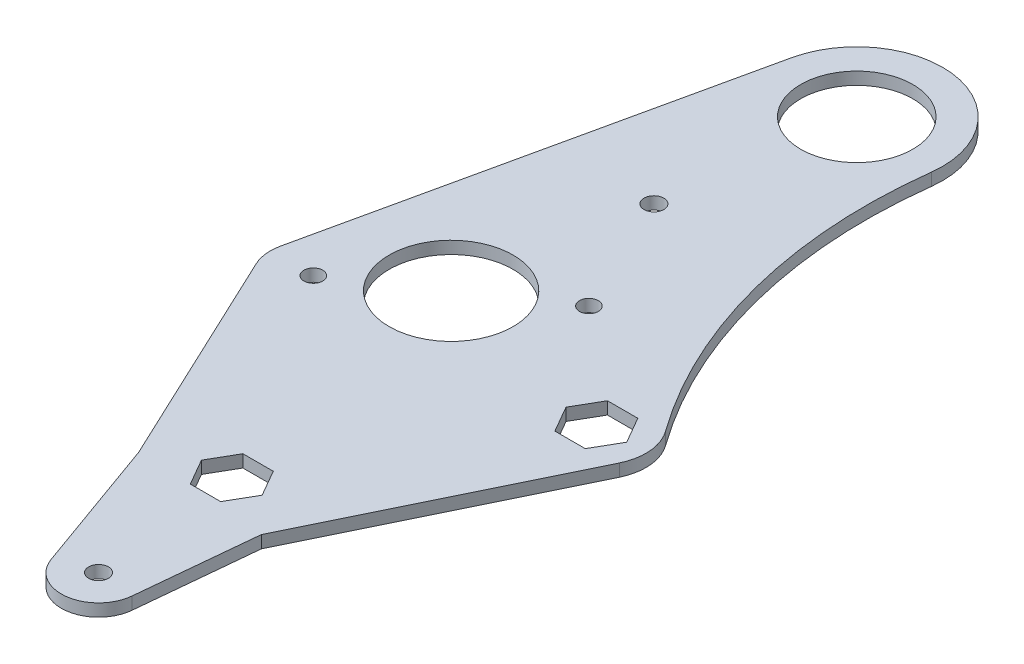
SolidWorks part; units mm, degrees
ref_plane "Front Plane" through (0, 0, 0) normal (0, 0, 1) x (1, 0, 0)
ref_plane "Top Plane" through (0, 0, 0) normal (0, 1, 0) x (1, 0, 0)
ref_plane "Right Plane" through (0, 0, 0) normal (1, 0, 0) x (0, 0, -1)
sketch "Sketch1" plane through (0, 0, 0) normal (0, 1, 0) x (1, 0, 0)
  line L0 (60.325, -101.6) -> (50.8, 0) construction
  line L1 (49.5334, -11.2731) -> (37.1501, -8.4548) construction
  line L2 (38.8111, -108.331) -> (42.6973, -101.6)
  line L3 (42.6973, -101.6) -> (38.8111, -94.869)
  line L4 (38.8111, -94.869) -> (31.0389, -94.869)
  line L5 (31.0389, -94.869) -> (27.1527, -101.6)
  line L6 (27.1527, -101.6) -> (31.0389, -108.331)
  line L7 (31.0389, -108.331) -> (38.8111, -108.331)
  line L12 (-34.3622, -104.78) -> (7.6653, -76.2435) construction
  line L13 (21.3295, 5.3232) -> (47.247, -98.5248) construction
  line L14 (50.9286, -81.8758) -> (59.0578, -71.8567) construction
  line L15 (0, 0) -> (37.1501, -8.4548) construction
  line L16 (34.925, -101.6) -> (59.0578, -71.8567) construction
  line L17 (49.5334, -11.2731) -> (99.0668, -22.5461) construction
  line L18 (99.0668, -22.5461) -> (50.9286, -81.8758) construction
  line L19 (46.3515, -107.1429) -> (16.404, -168.8788)
  line L20 (-25.4, -134.62) -> (25.4, -134.62) construction
  line L21 (-25.4, -134.62) -> (-25.4, -185.42) construction
  line L22 (-25.4, -185.42) -> (25.4, -185.42) construction
  line L23 (25.4, -134.62) -> (25.4, -185.42) construction
  line L24 (-25.4, -134.62) -> (25.4, -185.42) construction
  line L25 (-25.4, -185.42) -> (25.4, -134.62) construction
  line L26 (-45.1019, -102.4111) -> (-21.4676, 4.7353)
  line L27 (11.9515, -73.3332) -> (-29.0739, -64.2838) construction
  line L28 (11.9515, -73.3332) -> (2.377, -116.7398) construction
  line L29 (2.377, -116.7398) -> (-38.6485, -107.6904) construction
  line L30 (-29.0739, -64.2838) -> (-38.6485, -107.6904) construction
  line L31 (11.9515, -73.3332) -> (-38.6485, -107.6904) construction
  line L32 (2.377, -116.7398) -> (-29.0739, -64.2838) construction
  line L33 (-17.5479, -166.316) -> (-44.3125, -109.4645)
  line L34 (13.4626, -199.0444) -> (16.404, -168.8788)
  line L35 (-4.9829, -201.3367) -> (-17.5479, -166.316)
  line L36 (-13.3485, -90.5118) -> (0, 0) construction
  line L37 (-3.8861, -166.751) -> (3.8861, -166.751)
  line L38 (3.8861, -166.751) -> (7.7723, -160.02)
  line L39 (7.7723, -160.02) -> (3.8861, -153.289)
  line L40 (3.8861, -153.289) -> (-3.8861, -153.289)
  line L41 (-3.8861, -153.289) -> (-7.7723, -160.02)
  line L42 (-7.7723, -160.02) -> (-3.8861, -166.751)
  circle A0 centre (0, 0) radius 50.8 construction
  circle A1 centre (34.925, -101.6) radius 25.4 construction
  circle A2 centre (99.0668, -22.5461) radius 63.5 construction
  circle A3 centre (0, 0) radius 14.3637
  circle A4 centre (0, 0) radius 21.9837 construction
  circle A5 centre (34.925, -101.6) radius 6.731 construction
  circle A6 centre (34.925, -101.6) radius 12.7 construction
  arc A9 (47.247, -98.5248) -> (46.3515, -107.1429) centre (34.925, -101.6) cw
  arc A10 (-21.4676, 4.7353) -> (21.3295, 5.3232) centre (0, 0) cw
  circle A11 centre (3.9825, -198.12) radius 2.54
  circle A12 centre (3.9825, -198.12) radius 9.525 construction
  circle A14 centre (7.6653, -76.2435) radius 2.413
  circle A15 centre (-13.3485, -90.5118) radius 15.875
  circle A16 centre (-34.3622, -104.78) radius 2.413
  circle A17 centre (0, -160.02) radius 18.6432 construction
  arc A18 (-4.9829, -201.3367) -> (13.4626, -199.0444) centre (3.9825, -198.12) ccw
  arc A19 (-44.3125, -109.4645) -> (-45.1019, -102.4111) centre (-34.3622, -104.78) cw
  circle A20 centre (0, -160.02) radius 6.731 construction
  arc A21 (45.2316, -94.1796) -> (21.8179, -2.6949) centre (150.2634, -18.5602) cw
  arc A22 (21.8179, -2.6949) -> (21.3295, 5.3232) centre (0, 0) ccw
  arc A23 (45.2316, -94.1796) -> (46.0635, -107.7011) centre (34.925, -101.6) cw
  circle A24 centre (-6.6742, -45.2559) radius 2.54
  point P11 (99.0668, -151.13)
  point P24 (49.5334, -11.2731)
  point P28 (37.1501, -8.4548)
  point P35 (34.925, -127)
  dimension "D1" = 101.6
  dimension "D2" = 50.8
  dimension "D4" = 127
  dimension "D5" = 28.7274
  dimension "D7" = 13.462
  dimension "D9" = 25.4
  dimension "D15" = 5.08
  dimension "D16" = 19.05
  dimension "D19" = 4.826
  dimension "D20" = 31.75
  dimension "D11" = 5.08
  dimension "D25" = 38.1
  dimension "D3" = 9.525
  dimension "D8" = 101.6
  dimension "D10" = 160.02
  dimension "D12" = 12.7
  dimension "D13" = 50.8
  dimension "D14" = 50.8
  dimension "D17" = 91.4908
  dimension "D18" = 8.8588
  dimension "D21" = 50.8
  dimension "D22" = 44.45
  dimension "D23" = 42.0116
  dimension "D24" = 16.404
  dimension "D6" = 7.62
extrude "Boss-Extrude1" add sketch "Sketch1" along normal blind 3.175
sketch "Sketch2" [suppressed] plane through (0, 3.175, 0) normal (0, 1, 0) x (1, 0, 0)
  circle A0 centre (-13.3485, -90.5118) radius 22.225
  dimension "D1" = 44.45
extrude "Cut-Extrude1" [suppressed] cut sketch "Sketch2" against normal blind 1219.2
sketch "Sketch3" [suppressed] plane through (0, 3.175, 0) normal (0, 1, 0) x (1, 0, 0)
  circle A0 centre (-34.3622, -104.78) radius 2.413
  circle A1 centre (7.6653, -76.2435) radius 2.413
  circle A2 centre (7.6653, -76.2435) radius 2.413 construction
extrude "Boss-Extrude2" [suppressed] add sketch "Sketch3" against normal up to surface (3.175 mm away)
fillet "Fillet1" [suppressed] radius 3.175
sketch "Sketch4" [suppressed] plane through (0, 3.175, 0) normal (0, 1, 0) x (1, 0, 0)
  circle A0 centre (-11.6921, -139.7688) radius 2.15
  circle A1 centre (12.1204, -139.7688) radius 2.15
extrude "Cut-Extrude2" [suppressed] cut sketch "Sketch4" against normal blind 8.382
